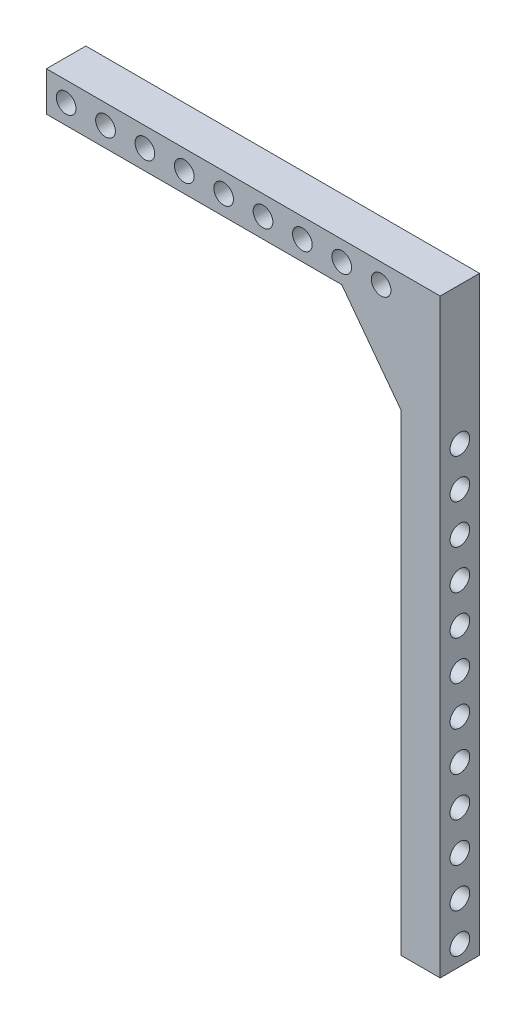
SolidWorks part; units mm, degrees
ref_plane "Plan de face" through (0, 0, 0) normal (0, 0, 1) x (1, 0, 0)
ref_plane "Plan de dessus" through (0, 0, 0) normal (0, 1, 0) x (1, 0, 0)
ref_plane "Plan de droite" through (0, 0, 0) normal (1, 0, 0) x (0, 0, -1)
sketch "Esquisse2" plane through (0, 0, 0) normal (1, 0, 0) x (0, 0, -1)
  line L1 (-5, -5) -> (5, -5)
  line L2 (-5, -5) -> (-5, 5)
  line L3 (-5, 5) -> (5, 5)
  line L4 (5, -5) -> (5, 5)
  line L5 (-5, -5) -> (5, 5) construction
  line L6 (-5, 5) -> (5, -5) construction
  point P0 (0, 0)
  dimension "D1" = 10
  dimension "D2" = 10
extrude "Boss.-Extru.1" add sketch "Esquisse2" along normal blind 90
sketch "Esquisse3" plane through (90, 0, 0) normal (1, 0, 0) x (0, 0, -1)
  line L0 (5, -5) -> (5, 5) construction
  line L1 (-5, 5) -> (5, 5)
  line L2 (-5, 5) -> (-5, -145)
  line L3 (-5, -145) -> (5, -145)
  line L4 (5, 5) -> (5, -145)
  line L5 (0, -145) -> (0, 5) construction
  circle A0 centre (0, -140) radius 2.5
  circle A1 centre (0, -130) radius 2.5
  circle A2 centre (0, -120) radius 2.5
  circle A3 centre (0, -110) radius 2.5
  circle A4 centre (0, -100) radius 2.5
  circle A5 centre (0, -90) radius 2.5
  circle A6 centre (0, -80) radius 2.5
  circle A7 centre (0, -70) radius 2.5
  circle A8 centre (0, -60) radius 2.5
  circle A9 centre (0, -50) radius 2.5
  circle A10 centre (0, -40) radius 2.5
  circle A11 centre (0, -30) radius 2.5
  dimension "D4" = 5
  dimension "D1" = 150
  dimension "D2" = 5
  dimension "D3" = 12
extrude "Boss.-Extru.2" add sketch "Esquisse3" along normal blind 10
sketch "Esquisse4" plane through (0, 0, -5) normal (0, 0, -1) x (-1, 0, 0)
  line L0 (0, 0) -> (-100, 0) construction
  line L1 (-100, -145) -> (-100, 5) construction
  line L2 (0, -5) -> (0, 5) construction
  circle A0 centre (-5, 0) radius 2.5
  circle A1 centre (-15, 0) radius 2.5
  circle A2 centre (-25, 0) radius 2.5
  circle A3 centre (-35, 0) radius 2.5
  circle A4 centre (-45, 0) radius 2.5
  circle A5 centre (-55, 0) radius 2.5
  circle A6 centre (-65, 0) radius 2.5
  circle A7 centre (-75, 0) radius 2.5
  circle A8 centre (-85, 0) radius 2.5
  dimension "D1" = 5
  dimension "D2" = 5
  dimension "D3" = 9
extrude "Enlèv. mat.-Extru.1" cut sketch "Esquisse4" against normal up to surface (10 mm away) up to face at (63.3333, -48.3333, 5)
sketch "Esquisse5" plane through (0, 0, -5) normal (0, 0, -1) x (-1, 0, 0)
  line L0 (-75, -5) -> (-90, -25)
  line L1 (-90, -5) -> (0, -5) construction
  line L2 (-90, -145) -> (-90, -5) construction
  line L3 (-90, -25) -> (-90, -5)
  line L4 (-90, -5) -> (-75, -5)
  dimension "D1" = 15
  dimension "D2" = 20
extrude "Boss.-Extru.3" add sketch "Esquisse5" against normal up to surface (10 mm away) up to face at (12.5, 0, 5)
